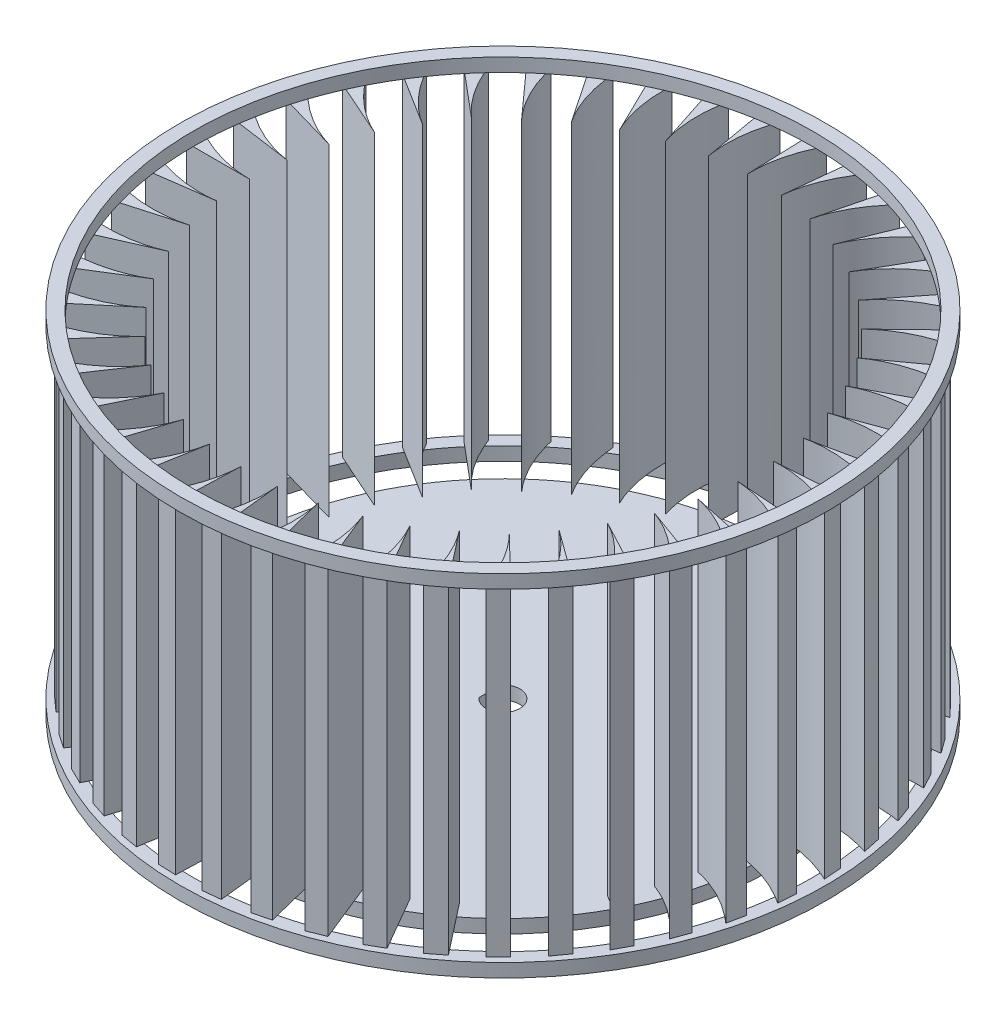
SolidWorks part; units mm, degrees
ref_plane "Front Plane" through (0, 0, 0) normal (0, 0, 1) x (1, 0, 0)
ref_plane "Top Plane" through (0, 0, 0) normal (0, 1, 0) x (1, 0, 0)
ref_plane "Right Plane" through (0, 0, 0) normal (1, 0, 0) x (0, 0, -1)
sketch "Sketch1" plane through (0, 0, 0) normal (0, 1, 0) x (1, 0, 0)
  circle A1 centre (0, 0) radius 76.2
  circle A2 centre (0, 0) radius 73.025
  dimension "D1" = 3.175
  dimension "D2" = 152.4
extrude "Boss-Extrude1" add sketch "Sketch1" along normal blind 3.175
sketch "Sketch3" plane through (0, 0, 0) normal (0, 1, 0) x (1, 0, 0)
  circle A0 centre (0, 0) radius 63.5
  dimension "D1" = 127
extrude "Boss-Extrude2" add sketch "Sketch3" along normal blind 3.175 separate body
sketch "Sketch4" plane through (0, 3.175, 0) normal (0, 1, 0) x (1, 0, 0)
  line L0 (-94.5477, 0) -> (94.5477, 0) construction
  line L1 (0, -97.8525) -> (0, 97.8525) construction
  line L2 (-3.048, -2.5911) -> (-3.048, 2.5911)
  arc A0 (-3.048, -2.5911) -> (-3.048, 2.5911) centre (0, 0) ccw
  point P6 (0, 0)
  point P10 (0, 0)
  point P12 (-3.048, 0)
  dimension "D1" = 8.001
  dimension "D3" = 3.048
extrude "Cut-Extrude1" cut sketch "Sketch4" against normal blind 3.175
sketch "Sketch5" plane through (0, 3.175, 0) normal (0, 1, 0) x (1, 0, 0)
  line L0 (-112.5344, 0) -> (112.5344, 0) construction
  line L1 (0, -80.4762) -> (0, 80.4762) construction
  line L2 (-74.6125, 0) -> (-59.4482, 0)
  line L3 (-74.6125, 0) -> (-74.6125, 4.151)
  line L4 (-72.982, 15.5128) -> (-58.1491, 12.36)
  line L5 (-72.982, 15.5128) -> (-72.119, 19.5731)
  line L6 (-68.1619, 30.3476) -> (-54.3086, 24.1798)
  line L7 (-68.1619, 30.3476) -> (-66.4736, 34.1397)
  line L8 (-60.3628, 43.8561) -> (-48.0946, 34.9428)
  line L9 (-60.3628, 43.8561) -> (-57.9229, 47.2143)
  line L10 (-49.9255, 55.4479) -> (-39.7786, 44.1786)
  line L11 (-49.9255, 55.4479) -> (-46.8407, 58.2254)
  line L12 (-37.3062, 64.6163) -> (-29.7241, 51.4836)
  line L13 (-37.3062, 64.6163) -> (-33.7114, 66.6918)
  line L14 (-23.0565, 70.9607) -> (-18.3705, 56.5386)
  line L15 (-23.0565, 70.9607) -> (-19.1087, 72.2434)
  line L16 (-7.7991, 74.2038) -> (-6.214, 59.1225)
  line L17 (-7.7991, 74.2038) -> (-3.6709, 74.6377)
  line L18 (7.7991, 74.2038) -> (6.214, 59.1225)
  line L19 (7.7991, 74.2038) -> (11.9273, 73.7699)
  line L20 (23.0565, 70.9607) -> (18.3705, 56.5386)
  line L21 (23.0565, 70.9607) -> (27.0043, 69.678)
  line L22 (37.3063, 64.6163) -> (29.7241, 51.4836)
  line L23 (37.3063, 64.6163) -> (40.9011, 62.5408)
  line L24 (49.9255, 55.4479) -> (39.7786, 44.1786)
  line L25 (49.9255, 55.4479) -> (53.0103, 52.6704)
  line L26 (60.3628, 43.8561) -> (48.0946, 34.9428)
  line L27 (60.3628, 43.8561) -> (62.8026, 40.4979)
  line L28 (68.1619, 30.3476) -> (54.3086, 24.1798)
  line L29 (68.1619, 30.3476) -> (69.8503, 26.5556)
  line L30 (72.982, 15.5128) -> (58.1491, 12.36)
  line L31 (72.982, 15.5128) -> (73.8451, 11.4526)
  line L32 (74.6125, 0) -> (59.4482, 0)
  line L33 (74.6125, 0) -> (74.6125, -4.151)
  line L34 (72.982, -15.5128) -> (58.1491, -12.36)
  line L35 (72.982, -15.5128) -> (72.119, -19.5731)
  line L36 (68.1619, -30.3476) -> (54.3086, -24.1798)
  line L37 (68.1619, -30.3476) -> (66.4736, -34.1397)
  line L38 (60.3628, -43.8561) -> (48.0946, -34.9428)
  line L39 (60.3628, -43.8561) -> (57.9229, -47.2143)
  line L40 (49.9255, -55.4479) -> (39.7786, -44.1786)
  line L41 (49.9255, -55.4479) -> (46.8407, -58.2254)
  line L42 (37.3062, -64.6163) -> (29.7241, -51.4836)
  line L43 (37.3062, -64.6163) -> (33.7114, -66.6918)
  line L44 (23.0565, -70.9607) -> (18.3705, -56.5386)
  line L45 (23.0565, -70.9607) -> (19.1087, -72.2434)
  line L46 (7.7991, -74.2038) -> (6.214, -59.1225)
  line L47 (7.7991, -74.2038) -> (3.6709, -74.6377)
  line L48 (-7.7991, -74.2038) -> (-6.214, -59.1225)
  line L49 (-7.7991, -74.2038) -> (-11.9273, -73.7699)
  line L50 (-23.0565, -70.9607) -> (-18.3705, -56.5386)
  line L51 (-23.0565, -70.9607) -> (-27.0043, -69.678)
  line L52 (-37.3063, -64.6163) -> (-29.7241, -51.4836)
  line L53 (-37.3063, -64.6163) -> (-40.9011, -62.5408)
  line L54 (-49.9255, -55.4479) -> (-39.7786, -44.1786)
  line L55 (-49.9255, -55.4479) -> (-53.0103, -52.6704)
  line L56 (-60.3628, -43.8561) -> (-48.0946, -34.9428)
  line L57 (-60.3628, -43.8561) -> (-62.8026, -40.4979)
  line L58 (-68.1619, -30.3476) -> (-54.3086, -24.1798)
  line L59 (-68.1619, -30.3476) -> (-69.8503, -26.5556)
  line L60 (-72.982, -15.5128) -> (-58.1491, -12.36)
  line L61 (-72.982, -15.5128) -> (-73.8451, -11.4526)
  spline S0 degree 2 poles (-74.6125, 4.151) (-67.1407, -0.0412) (-59.4482, 0) knots 0 0 0 0.62178 0.62178 0.62178
  spline S1 degree 2 poles (-72.119, 19.5731) (-65.6821, 13.919) (-58.1491, 12.36) knots 0 0 0 0.62178 0.62178 0.62178
  spline S2 degree 2 poles (-66.4736, 34.1397) (-61.3528, 27.2709) (-54.3086, 24.1798) knots 0 0 0 0.62178 0.62178 0.62178
  spline S3 degree 2 poles (-57.9229, 47.2143) (-54.3422, 39.431) (-48.0946, 34.9428) knots 0 0 0 0.62178 0.62178 0.62178
  spline S4 degree 2 poles (-46.8407, 58.2254) (-44.9565, 49.8677) (-39.7786, 44.1786) knots 0 0 0 0.62178 0.62178 0.62178
  spline S5 degree 2 poles (-33.7114, 66.6918) (-33.606, 58.1249) (-29.7241, 51.4836) knots 0 0 0 0.62178 0.62178 0.62178
  spline S6 degree 2 poles (-19.1087, 72.2434) (-20.7868, 63.8419) (-18.3705, 56.5386) knots 0 0 0 0.62178 0.62178 0.62178
  spline S7 degree 2 poles (-3.6709, 74.6377) (-7.0591, 66.7686) (-6.214, 59.1225) knots 0 0 0 0.62178 0.62178 0.62178
  spline S8 degree 2 poles (11.9273, 73.7699) (6.9771, 66.7772) (6.214, 59.1225) knots 0 0 0 0.62178 0.62178 0.62178
  spline S9 degree 2 poles (27.0043, 69.678) (20.7084, 63.8673) (18.3705, 56.5386) knots 0 0 0 0.62178 0.62178 0.62178
  spline S10 degree 2 poles (40.9011, 62.5408) (33.5347, 58.1661) (29.7241, 51.4836) knots 0 0 0 0.62178 0.62178 0.62178
  spline S11 degree 2 poles (53.0103, 52.6704) (44.8953, 49.9228) (39.7786, 44.1786) knots 0 0 0 0.62178 0.62178 0.62178
  spline S12 degree 2 poles (62.8026, 40.4979) (54.2937, 39.4976) (48.0946, 34.9428) knots 0 0 0 0.62178 0.62178 0.62178
  spline S13 degree 2 poles (69.8503, 26.5556) (61.3193, 27.3462) (54.3086, 24.1798) knots 0 0 0 0.62178 0.62178 0.62178
  spline S14 degree 2 poles (73.8451, 11.4526) (65.6649, 13.9996) (58.1491, 12.36) knots 0 0 0 0.62178 0.62178 0.62178
  spline S15 degree 2 poles (74.6125, -4.151) (67.1407, 0.0412) (59.4482, 0) knots 0 0 0 0.62178 0.62178 0.62178
  spline S16 degree 2 poles (72.119, -19.5731) (65.6821, -13.919) (58.1491, -12.36) knots 0 0 0 0.62178 0.62178 0.62178
  spline S17 degree 2 poles (66.4736, -34.1397) (61.3528, -27.2709) (54.3086, -24.1798) knots 0 0 0 0.62178 0.62178 0.62178
  spline S18 degree 2 poles (57.9229, -47.2143) (54.3422, -39.431) (48.0946, -34.9428) knots 0 0 0 0.62178 0.62178 0.62178
  spline S19 degree 2 poles (46.8407, -58.2254) (44.9565, -49.8677) (39.7786, -44.1786) knots 0 0 0 0.62178 0.62178 0.62178
  spline S20 degree 2 poles (33.7114, -66.6918) (33.606, -58.1249) (29.7241, -51.4836) knots 0 0 0 0.62178 0.62178 0.62178
  spline S21 degree 2 poles (19.1087, -72.2434) (20.7868, -63.8419) (18.3705, -56.5386) knots 0 0 0 0.62178 0.62178 0.62178
  spline S22 degree 2 poles (3.6709, -74.6377) (7.0591, -66.7686) (6.214, -59.1225) knots 0 0 0 0.62178 0.62178 0.62178
  spline S23 degree 2 poles (-11.9273, -73.7699) (-6.9771, -66.7772) (-6.214, -59.1225) knots 0 0 0 0.62178 0.62178 0.62178
  spline S24 degree 2 poles (-27.0043, -69.678) (-20.7084, -63.8673) (-18.3705, -56.5386) knots 0 0 0 0.62178 0.62178 0.62178
  spline S25 degree 2 poles (-40.9011, -62.5408) (-33.5347, -58.1661) (-29.7241, -51.4836) knots 0 0 0 0.62178 0.62178 0.62178
  spline S26 degree 2 poles (-53.0103, -52.6704) (-44.8953, -49.9228) (-39.7786, -44.1786) knots 0 0 0 0.62178 0.62178 0.62178
  spline S27 degree 2 poles (-62.8026, -40.4979) (-54.2937, -39.4976) (-48.0946, -34.9428) knots 0 0 0 0.62178 0.62178 0.62178
  spline S28 degree 2 poles (-69.8503, -26.5556) (-61.3193, -27.3462) (-54.3086, -24.1798) knots 0 0 0 0.62178 0.62178 0.62178
  spline S29 degree 2 poles (-73.8451, -11.4526) (-65.6649, -13.9996) (-58.1491, -12.36) knots 0 0 0 0.62178 0.62178 0.62178
  point P6 (0, 0)
  point P10 (0, 0)
  point P102 (0, 0)
  circle M2 centre (0, 0) radius 73.025
  dimension "D1" = 74.6125
  dimension "D2" = 30
extrude "Boss-Extrude3" add sketch "Sketch5" along normal blind 76.2 contours S0 L3 L2 M2 | S0 L2 M2
pattern_circular "CirPattern2" count 45 over 360 about axis through (0, 3.175, 0) along (0, 1, 0) of "Boss-Extrude3"
sketch "Sketch6" plane through (0, 79.375, 0) normal (0, 1, 0) x (1, 0, 0)
  circle A0 centre (0, 0) radius 76.2
  circle A1 centre (0, 0) radius 73.025
  dimension "D1" = 3.175
extrude "Boss-Extrude4" add sketch "Sketch6" along normal blind 3.175
